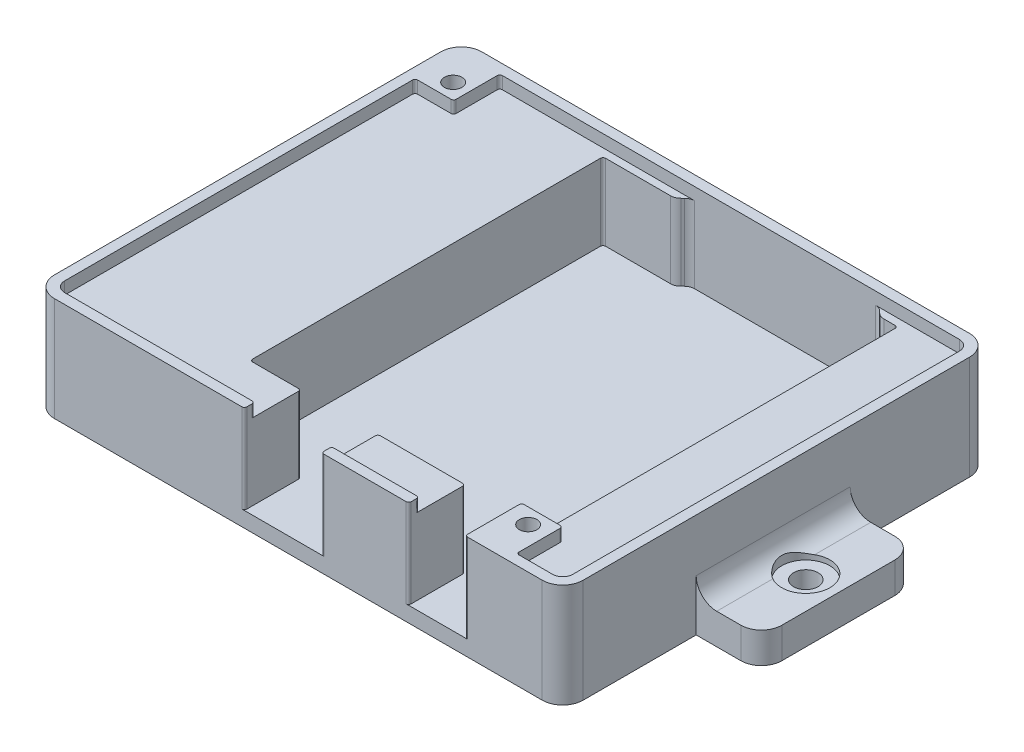
SolidWorks part; units mm, degrees
ref_plane "Front Plane" through (0, 0, 0) normal (0, 0, 1) x (1, 0, 0)
ref_plane "Top Plane" through (0, 0, 0) normal (0, 1, 0) x (1, 0, 0)
ref_plane "Right Plane" through (0, 0, 0) normal (1, 0, 0) x (0, 0, -1)
sketch "Sketch1" plane through (0, 0, 0) normal (0, 1, 0) x (1, 0, 0)
  line L1 (0, 0) -> (103, 0)
  line L2 (0, 0) -> (0, 83.25)
  line L3 (0, 83.25) -> (103, 83.25)
  line L4 (103, 0) -> (103, 83.25)
  dimension "D1" = 83.25
  dimension "D2" = 103
extrude "Boss-Extrude1" add sketch "Sketch1" along normal blind 20.2438
sketch "Sketch2" plane through (0, 20.2438, 0) normal (0, 1, 0) x (1, 0, 0)
  line L0 (0, 83.25) -> (0, 0) construction
  line L1 (31.1, 79.75) -> (45.1, 79.75)
  line L2 (31.1, 79.75) -> (31.1, 11)
  line L3 (31.1, 11) -> (88.5, 11)
  line L4 (88.5, 79.75) -> (88.5, 11)
  line L5 (103, 83.25) -> (0, 83.25) construction
  line L6 (85, 79.75) -> (88.5, 79.75)
  line L8 (45.85, 80.5) -> (45.85, 81.25) construction
  line L9 (46.6, 81.25) -> (83.5, 81.25)
  line L10 (84.25, 80.5) -> (84.25, 81.25) construction
  line L11 (103, 0) -> (103, 83.25) construction
  line L12 (45.1, 79.75) -> (46.6, 81.25)
  line L13 (85, 79.75) -> (83.5, 81.25)
  line L14 (84.25, 79.75) -> (84.25, 80.5) construction
  line L15 (84.25, 79.75) -> (85, 79.75) construction
  line L16 (83.5, 81.25) -> (84.25, 81.25) construction
  line L17 (45.1, 79.75) -> (45.85, 79.75) construction
  line L18 (45.85, 79.75) -> (45.85, 80.5) construction
  line L19 (45.85, 81.25) -> (46.6, 81.25) construction
  point P18 (84.25, 80.5)
  point P19 (45.85, 80.5)
  dimension "D1" = 31.1
  dimension "D2" = 3.5
  dimension "D3" = 2
  dimension "D4" = 14.75
  dimension "D5" = 4.25
  dimension "D6" = 68.75
  dimension "D7" = 14.5
  dimension "D8" = 38.4
  dimension "D9" = 45
  dimension "D10" = 45
extrude "Cut-Extrude1" cut sketch "Sketch2" against normal offset from surface (17.2438 mm away) 3 up to face at (51.5, 0, -41.625)
sketch "Sketch3" plane through (0, 0, 0) normal (0, 0, 1) x (1, 0, 0)
  line L0 (0, 20.2438) -> (103, 20.2438) construction
  line L1 (41, 20.2438) -> (56, 20.2438)
  line L2 (41, 20.2438) -> (41, 3)
  line L3 (41, 3) -> (56, 3)
  line L4 (56, 20.2438) -> (56, 3)
  line L5 (0, 20.2438) -> (0, 0) construction
  line L6 (73, 20.2438) -> (84, 20.2438)
  line L7 (73, 20.2438) -> (73, 3)
  line L8 (73, 3) -> (84, 3)
  line L9 (84, 20.2438) -> (84, 3)
  line L10 (31.1, 3) -> (88.5, 3) construction
  dimension "D1" = 17.2438
  dimension "D2" = 15
  dimension "D3" = 41
  dimension "D4" = 11
  dimension "D6" = 17
extrude "Cut-Extrude2" cut sketch "Sketch3" against normal blind 14.9225
sketch "Sketch4" plane through (0, 20.2438, 0) normal (0, 1, 0) x (1, 0, 0)
  line L0 (0, 83.25) -> (0, 0) construction
  line L1 (9.5, 81.25) -> (101, 81.25)
  line L2 (2, 72.25) -> (2, 2)
  line L3 (2, 2) -> (84, 2)
  line L4 (101, 81.25) -> (101, 2)
  line L5 (0, 0) -> (41, 0) construction
  line L6 (2, 72.25) -> (9.5, 72.25)
  line L7 (9.5, 72.25) -> (9.5, 81.25)
  line L8 (92, 2) -> (92, 11)
  line L9 (92, 11) -> (84, 11)
  line L10 (84, 11) -> (84, 2)
  line L11 (84, 11) -> (84, 0) construction
  line L12 (92, 2) -> (101, 2)
  line L13 (103, 0) -> (103, 83.25) construction
  line L14 (103, 83.25) -> (0, 83.25) construction
  dimension "D1" = 2
  dimension "D2" = 2
  dimension "D3" = 2
  dimension "D4" = 2
  dimension "D5" = 9.5
  dimension "D6" = 11
  dimension "D7" = 8
  dimension "D8" = 11
  dimension "D9" = 19
extrude "Cut-Extrude3" cut sketch "Sketch4" against normal blind 2.4
sketch "Sketch5" plane through (0, 0, 0) normal (-1, 0, 0) x (0, 0, 1)
  line L0 (-83.25, 0) -> (0, 0) construction
  line L1 (-56, 0) -> (-26, 0)
  line L2 (-56, 0) -> (-56, 6)
  line L3 (-56, 6) -> (-26, 6)
  line L4 (-26, 0) -> (-26, 6)
  line L6 (0, 20.2438) -> (0, 0) construction
  dimension "D1" = 30
  dimension "D2" = 26
  dimension "D3" = 6
extrude "Boss-Extrude2" add sketch "Sketch5" along normal blind 12.7
ref_plane "Plane1" through (51.5, 0, 0) normal (-1, 0, 0) x (0, 0, 1)
mirror "Mirror1" about plane through (51.5, 0, 0) normal (-1, 0, 0) of "Boss-Extrude2"
sketch "Sketch6" plane through (0, 0, -83.25) normal (0, 0, -1) x (-1, 0, 0)
  line L0 (-103, 0) -> (0, 0) construction
  line L1 (-66.5, 0) -> (-36.5, 0)
  line L2 (-66.5, 0) -> (-66.5, 6)
  line L3 (-66.5, 6) -> (-36.5, 6)
  line L4 (-36.5, 0) -> (-36.5, 6)
  line L6 (-66.5, 0) -> (-36.5, 6) construction
  line L7 (-51.5, -11.1341) -> (-51.5, 11.1341) construction
  point P8 (-51.5, 3)
  dimension "D1" = 30
  dimension "D2" = 6
extrude "Boss-Extrude3" add sketch "Sketch6" along normal blind 12.7
fillet "Fillet1" radius 4 4 edges at (103, 10.1219, 0) (103, 10.1219, -83.25) (0, 10.1219, -83.25) (0, 10.1219, 0)
fillet "Fillet2" radius 0.5 20 edges at (41, 10.4219, -11) (56, 10.4219, -11) (73, 10.4219, -11) (92, 19.0438, -11) (84, 11.6219, -11) (9.5, 19.0438, -72.25) (84, 11.6219, 0) (56, 19.0438, -2) (41, 19.0438, -2) (73, 19.0438, -2) (73, 11.6219, 0) (56, 11.6219, 0) (41, 11.6219, 0) (92, 19.0438, -2) (9.5, 19.0438, -81.25) (2, 19.0438, -72.25) (88.5, 10.4219, -11) (31.1, 10.4219, -11) (31.1, 10.4219, -79.75) (88.5, 10.4219, -79.75)
fillet "Fillet3" radius 2 3 edges at (101, 19.0438, -81.25) (101, 19.0438, -2) (2, 19.0438, -2)
fillet "Fillet4" radius 4 9 edges at (0, 6, -41) (51.5, 6, -83.25) (103, 6, -41) (115.7, 3, -26) (115.7, 3, -56) (66.5, 3, -95.95) (36.5, 3, -95.95) (-12.7, 3, -56) (-12.7, 3, -26)
fillet "Fillet5" radius 2 4 edges at (45.1, 10.4219, -79.75) (46.6, 10.4219, -81.25) (85, 10.4219, -79.75) (83.5, 10.4219, -81.25)
sketch "Sketch7" plane through (0, 20.2438, 0) normal (0, 1, 0) x (1, 0, 0)
  line L1 (88.265, 8.0025) -> (6.35, 8.0025) construction
  line L2 (88.265, 8.0025) -> (88.265, 75.3125) construction
  line L3 (88.265, 75.3125) -> (6.35, 75.3125) construction
  line L4 (6.35, 8.0025) -> (6.35, 75.3125) construction
  line L5 (88.265, 8.0025) -> (6.35, 75.3125) construction
  line L6 (88.265, 75.3125) -> (6.35, 8.0025) construction
  line L8 (99, 83.25) -> (4, 83.25) construction
  line L9 (0, 79.25) -> (0, 4) construction
  line L10 (84.5, 11) -> (91.5, 11) construction
  line L12 (103, 4) -> (103, 79.25) construction
  circle A0 centre (6.35, 75.3125) radius 1.7145
  circle A1 centre (88.265, 8.0025) radius 1.7145
  point P2 (88, 5.1012)
  point P4 (47.3075, 41.6575)
  point P5 (46.7592, 41.3486)
  point P10 (97.2022, 17.1328)
  dimension "D1" = 3.429
  dimension "D2" = 7.9375
  dimension "D3" = 6.35
  dimension "D4" = 2.9975
  dimension "D5" = 14.735
  dimension "D6" = 67.31
  dimension "D7" = 81.915
extrude "Cut-Extrude4" cut sketch "Sketch7" against normal through all
sketch "Sketch8" plane through (0, 0, 0) normal (0, -1, 0) x (1, 0, 0)
  circle A0 centre (6.35, -75.3125) radius 3.81
  circle A1 centre (88.265, -8.0025) radius 3.81
  dimension "D1" = 7.62
extrude "Cut-Extrude5" cut sketch "Sketch8" against normal blind 3.302
sketch "Sketch11" plane through (0, 6, 0) normal (0, 1, 0) x (1, 0, 0)
  line L0 (-6.35, 56) -> (-6.35, 26) construction
  line L1 (-8.7, 56) -> (-4, 56) construction
  line L2 (-8.7, 26) -> (-4, 26) construction
  line L3 (36.5, 89.6) -> (66.5, 89.6) construction
  line L4 (36.5, 91.95) -> (36.5, 87.25) construction
  line L5 (66.5, 91.95) -> (66.5, 87.25) construction
  line L6 (-12.7, 30) -> (-12.7, 52) construction
  line L7 (-6.35, 41) -> (-12.7, 41) construction
  line L8 (51.5, 89.6) -> (51.5, 95.95) construction
  line L9 (109.35, 41) -> (115.7, 41) construction
  line L10 (115.7, 30) -> (115.7, 52) construction
  line L11 (40.5, 95.95) -> (62.5, 95.95) construction
  circle A0 centre (-6.35, 41) radius 2.3812
  circle A1 centre (51.5, 89.6) radius 2.3812
  circle A2 centre (109.35, 41) radius 2.3813
  point P12 (51.5, 89.6)
  point P13 (-6.35, 41)
  point P28 (51.5, 89.6)
  point P31 (109.35, 41)
  point P32 (-6.35, 41)
  dimension "D1" = 4.7625
  dimension "D2" = 6.35
extrude "Cut-Extrude7" cut sketch "Sketch11" against normal through all contours A0
sketch "Sketch12" plane through (0, 6, 0) normal (0, 1, 0) x (1, 0, 0)
  circle A0 centre (-6.35, 41) radius 4.699
  dimension "D1" = 9.398
extrude "Cut-Extrude8" cut sketch "Sketch12" against normal blind 1 and the other way through all
pattern_sketch "Sketch-Pattern2" of "Cut-Extrude7", "Cut-Extrude8" driven by "Sketch11"
